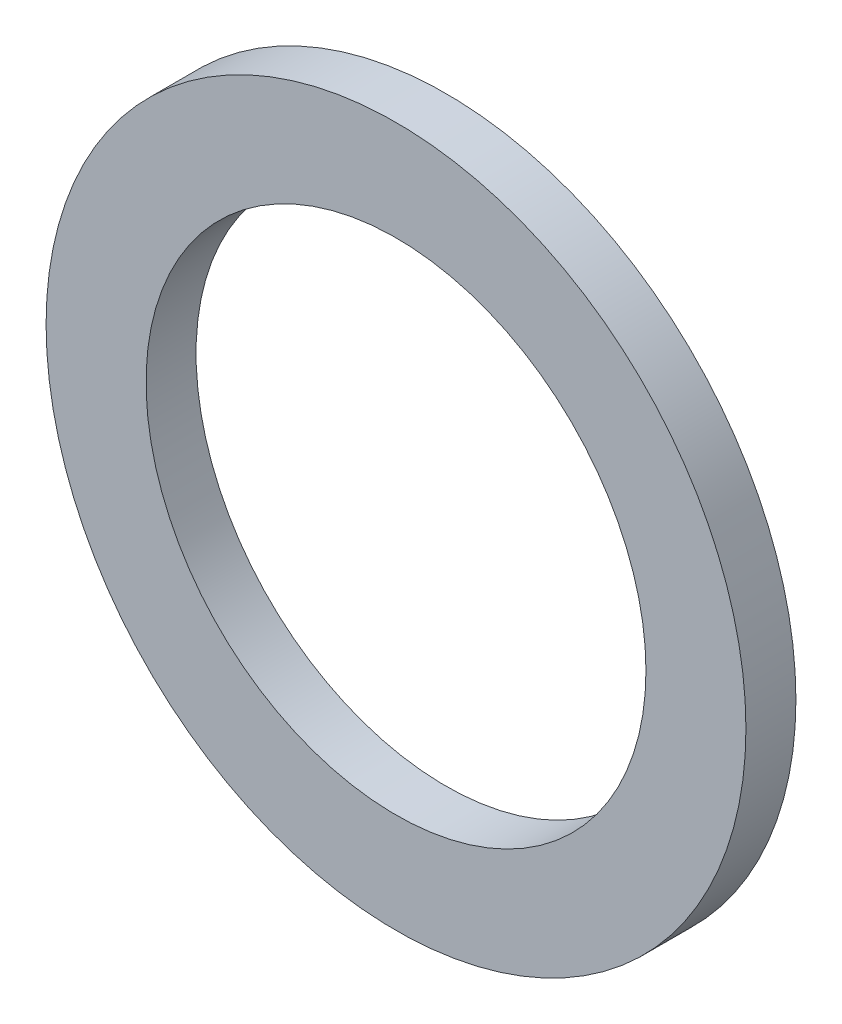
SolidWorks part; units mm, degrees
material "AISI 304"
ref_plane "前视基准面" through (0, 0, 0) normal (0, 0, 1) x (1, 0, 0)
ref_plane "上视基准面" through (0, 0, 0) normal (0, 1, 0) x (1, 0, 0)
ref_plane "右视基准面" through (0, 0, 0) normal (1, 0, 0) x (0, 0, -1)
sketch "草图1" plane through (0, 0, 0) normal (0, 0, 1) x (1, 0, 0)
  circle A0 centre (0, 0) radius 2.5
  circle A1 centre (0, 0) radius 3.5
  dimension "D1" = 5
  dimension "D2" = 7
extrude "凸台-拉伸1" add sketch "草图1" along normal blind 0.5
